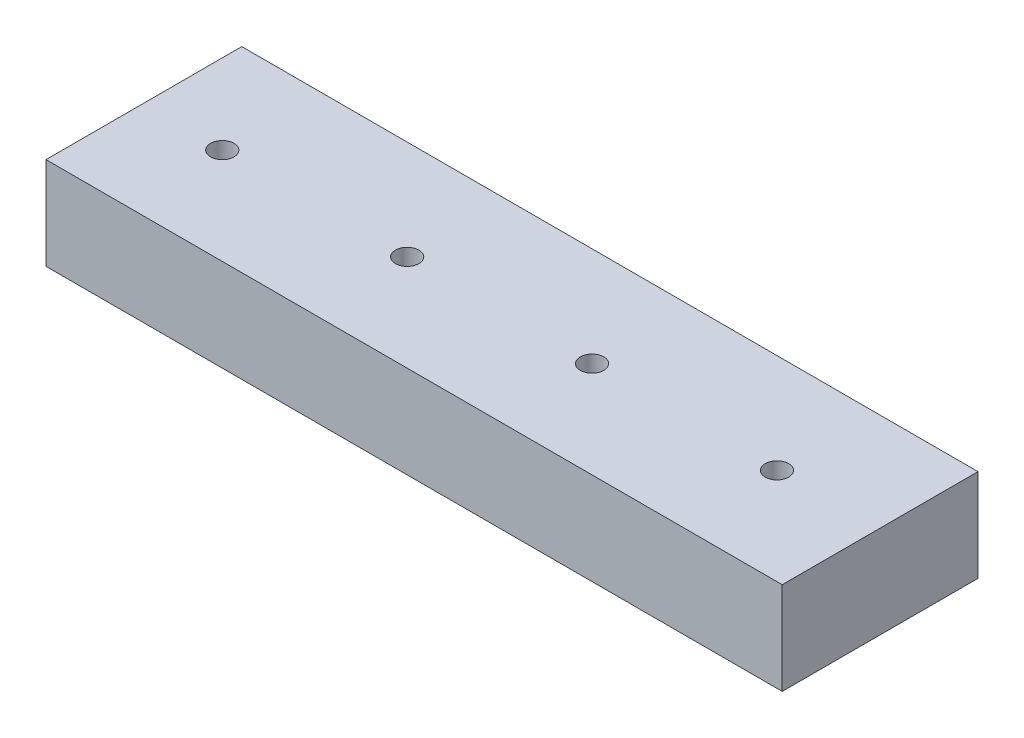
SolidWorks part; units mm, degrees
ref_plane "Front Plane" through (0, 0, 0) normal (0, 0, 1) x (1, 0, 0)
ref_plane "Top Plane" through (0, 0, 0) normal (0, 1, 0) x (1, 0, 0)
ref_plane "Right Plane" through (0, 0, 0) normal (1, 0, 0) x (0, 0, -1)
sketch "Sketch1" plane through (0, 0, 0) normal (0, 1, 0) x (1, 0, 0)
  line L0 (-20, 0) -> (0, 0)
  line L1 (0, 0) -> (20, 0)
  line L2 (20, 0) -> (40, 0)
  line L4 (-28.6433, 10.7542) -> (50.9906, 10.7542)
  line L5 (-28.6433, 10.7542) -> (-28.6433, -10.4243)
  line L6 (-28.6433, -10.4243) -> (50.9906, -10.4243)
  line L7 (50.9906, 10.7542) -> (50.9906, -10.4243)
  circle A0 centre (0, 0) radius 1.27
  circle A1 centre (-20, 0) radius 1.27
  circle A2 centre (20, 0) radius 1.27
  circle A3 centre (40, 0) radius 1.27
  dimension "D1" = 2.54
  dimension "D2" = 2.54
  dimension "7.7" = 2.54
  dimension "D3" = 2.54
  dimension "D4" = 20
extrude "Boss-Extrude1" add sketch "Sketch1" along normal blind 10
